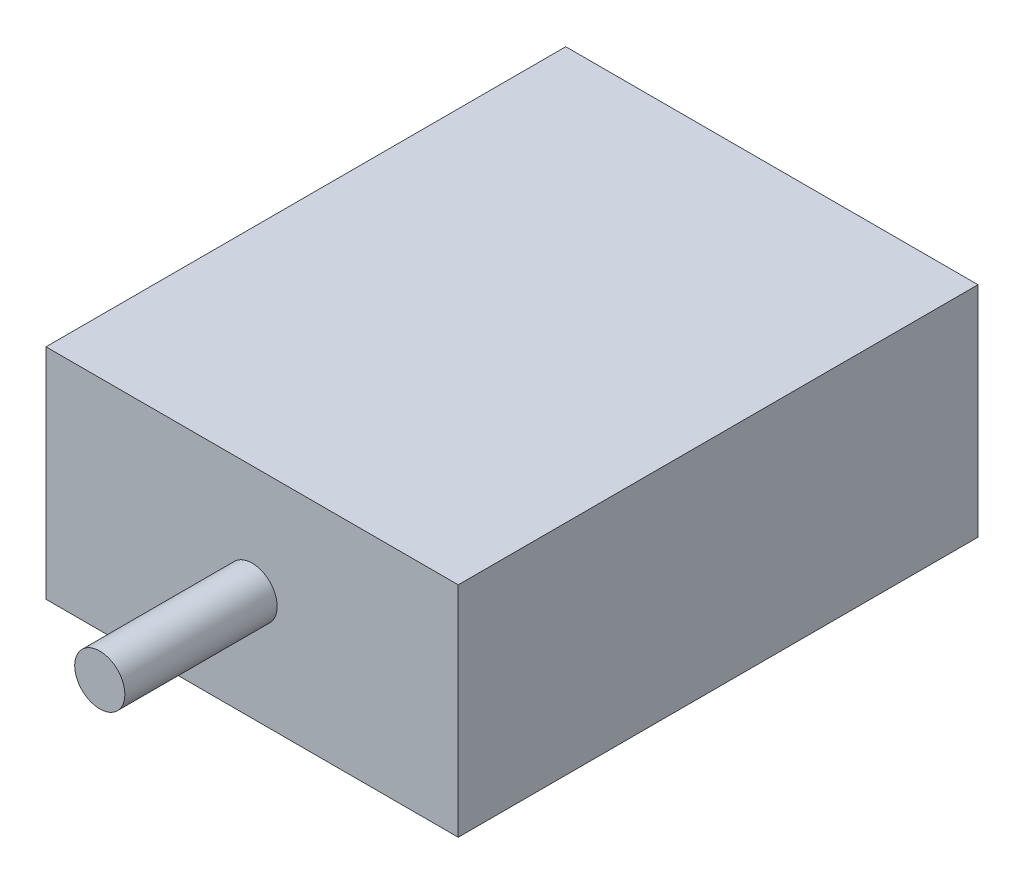
SolidWorks part; units mm, degrees
ref_plane "Front Plane" through (0, 0, 0) normal (0, 0, 1) x (1, 0, 0)
ref_plane "Top Plane" through (0, 0, 0) normal (0, 1, 0) x (1, 0, 0)
ref_plane "Right Plane" through (0, 0, 0) normal (1, 0, 0) x (0, 0, -1)
other "Configuration Table"
sketch "Sketch2" plane through (0, 0, 0) normal (0, 0, 1) x (1, 0, 0)
  line L1 (-11.5, -6.1) -> (11.5, -6.1)
  line L2 (-11.5, -6.1) -> (-11.5, 6.1)
  line L3 (-11.5, 6.1) -> (11.5, 6.1)
  line L4 (11.5, -6.1) -> (11.5, 6.1)
extrude "SG90_reference_envelope" add sketch "Sketch2" along normal blind 29 from offset 0
sketch "Sketch3" plane through (0, 0, 0) normal (0, 0, 1) x (1, 0, 0)
  circle A0 centre (0, 0) radius 1.4
extrude "Output_axis_REFERENCE_NOT_VENDOR_GEOMETRY" add sketch "Sketch3" along normal blind 8.5 from offset 29
